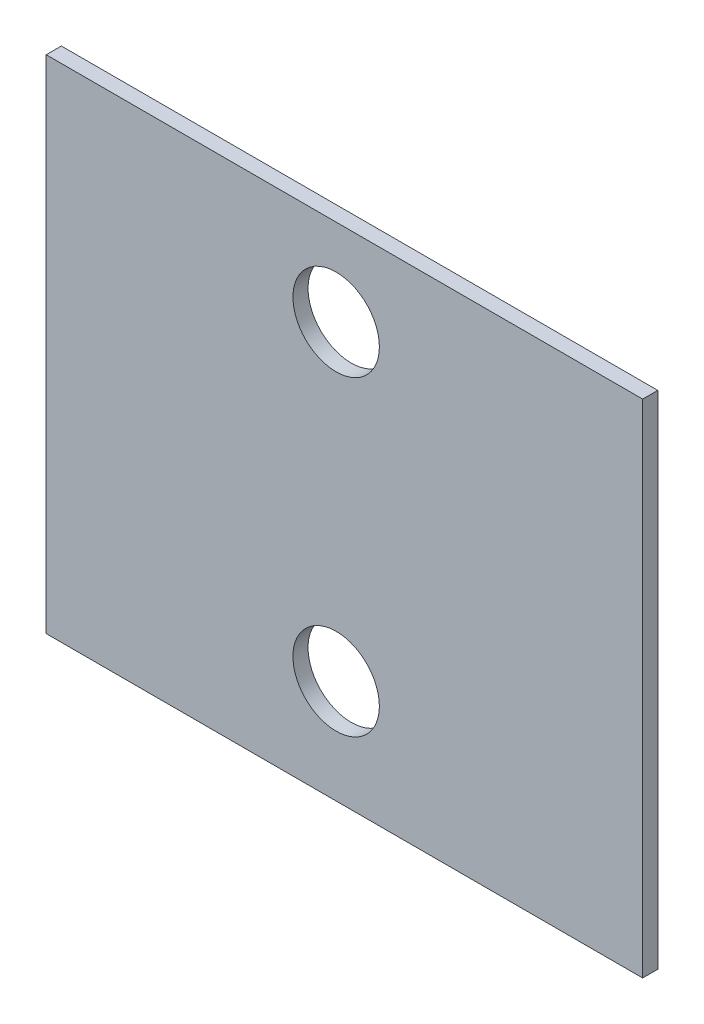
SolidWorks part; units mm, degrees
ref_plane "Front Plane" through (0, 0, 0) normal (0, 0, 1) x (1, 0, 0)
ref_plane "Top Plane" through (0, 0, 0) normal (0, 1, 0) x (1, 0, 0)
ref_plane "Right Plane" through (0, 0, 0) normal (1, 0, 0) x (0, 0, -1)
sketch "Sketch1" plane through (0, 0, 0) normal (0, 0, 1) x (1, 0, 0)
  line L6 (-36.5, 27.5) -> (32.5, 27.5)
  line L7 (-36.5, 27.5) -> (-36.5, -30.5)
  line L8 (-36.5, -30.5) -> (32.5, -30.5)
  line L9 (32.5, 27.5) -> (32.5, -30.5)
  circle A0 centre (-2.9584, 17.5) radius 5
  circle A1 centre (-2.9584, -18.5) radius 5
  point P4 (1.7053, 1.75)
  dimension "D3" = 10
  dimension "D4" = 10
  dimension "D1" = 69
  dimension "D2" = 10
  dimension "D5" = 69
  dimension "D6" = 58
  dimension "D7" = 36
extrude "Boss-Extrude1" add sketch "Sketch1" along normal blind 1.75
